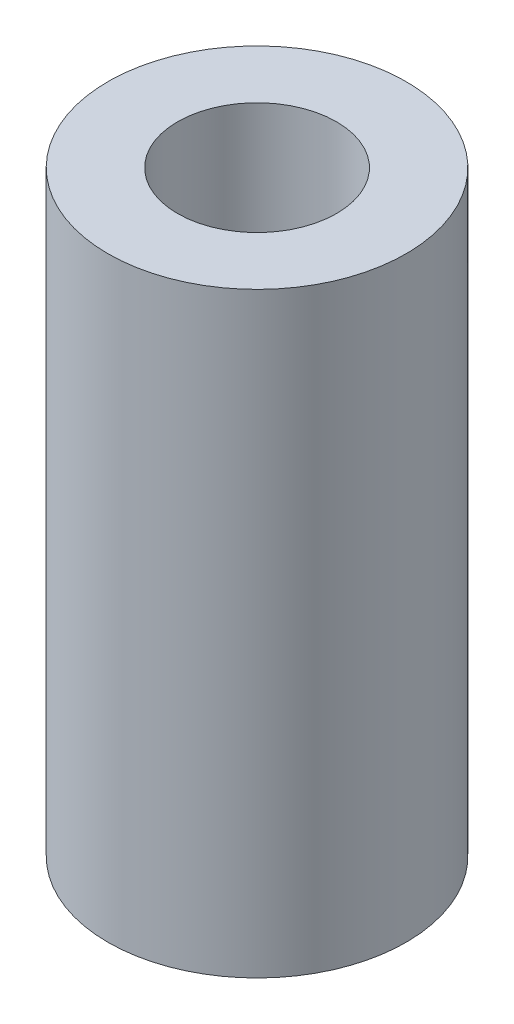
SolidWorks part; units mm, degrees
material "ABS"
ref_plane "Front Plane" through (0, 0, 0) normal (0, 0, 1) x (1, 0, 0)
ref_plane "Top Plane" through (0, 0, 0) normal (0, 1, 0) x (1, 0, 0)
ref_plane "Right Plane" through (0, 0, 0) normal (1, 0, 0) x (0, 0, -1)
sketch "Sketch1" plane through (0, 0, 0) normal (0, 1, 0) x (1, 0, 0)
  circle A0 centre (0, 0) radius 1.6
  circle A1 centre (0, 0) radius 3
  dimension "D1" = 3.2
  dimension "D2" = 6
extrude "Boss-Extrude1" add sketch "Sketch1" along normal mid plane 12
